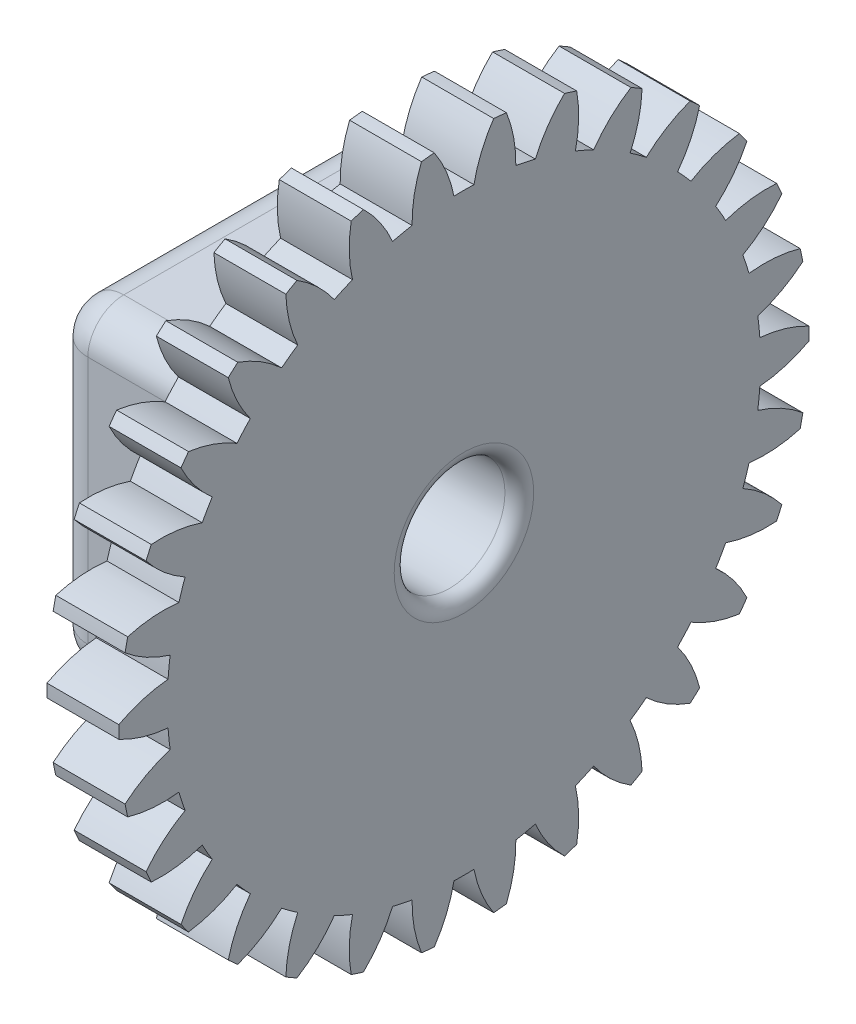
SolidWorks part; units mm, degrees
material "Custom Plastic"
ref_plane "Plane1" through (0, 0, 0) normal (0, 0, 1) x (1, 0, 0)
ref_plane "Plane2" through (0, 0, 0) normal (0, 1, 0) x (1, 0, 0)
ref_plane "Plane3" through (0, 0, 0) normal (1, 0, 0) x (0, 0, -1)
other "Configuration Table"
sketch "HoldingSke" plane through (0, 0, 0) normal (0, 1, 0) x (1, 0, 0)
  line L0 (0, 0) -> (0.2887, -0.1667)
  line L1 (-15, 0) -> (100, 0) construction
  line L2 (0, 0) -> (-2.1039, 2.3779)
  line L3 (0, 0) -> (-11.863, 4.5341)
  line L4 (0, 0) -> (7.479, 4.318)
  line L5 (0, 0) -> (-46.8476, -17.4728)
  line L6 (0, 0) -> (-8.2896, -5.593)
  line L7 (-2.1039, 2.3779) -> (8.6586, 51.2059)
  line L8 (-76.2, 54.61) -> (-74.4, 54.61)
  line L9 (-71.009, 38.7566) -> (-53.1078, 45.2721)
  line L10 (-76.2, 71.12) -> (104.1128, 71.12)
  line L11 (0, 0) -> (-10, 0)
  line L12 (-76.2, 101.6) -> (-76.093, 101.6)
  line L13 (24.9733, 27.94) -> (52.9518, 28.4284)
  line L14 (24.9733, 27.94) -> (24.9743, 27.94)
  line L15 (24.9733, 27.94) -> (100.4006, 29.5858)
  line L16 (-63.627, -3) -> (-12.827, -3)
  circle A0 centre (0, 0) radius 5
  circle A1 centre (0, 0) radius 37.5
  circle A2 centre (0, 0) radius 37.5
  circle A3 centre (0, 0) radius 5
  dimension "MHD" = 75
  dimension "Hub_dia" = 75
  dimension "Bore" = 10
  dimension "MBD" = 10
  dimension "Num_teeth" = 30
  dimension "Pitch" = 0.3333
  dimension "Overall_len" = 50
  dimension "Show_teeth" = 30
  dimension "Thickness" = 10
  dimension "OAL" = 50.0001
  dimension "T_dim" = 1.8
  dimension "Ap" = 20
  dimension "H" = 19.05
  dimension "Pitch_radius" = 180.3128
  dimension "Width" = 10
  dimension "Backlash" = 0.107
  dimension "Addendum_fac" = 1
  dimension "Dedendum_fac" = 1.25
  dimension "Clearance_fac" = 0.25
  dimension "Dedendum_add" = 0.001
  dimension "Module" = 3
sketch "BasProSke" plane through (0, 0, 0) normal (0, 1, 0) x (1, 0, 0)
  line L0 (-10, 0) -> (60, 0) construction
  line L1 (0, 0) -> (0, 48)
  line L2 (0, 0) -> (10, 0)
  line L3 (10, 0) -> (10, 48)
  line L4 (10, 48) -> (0, 48)
  dimension "Thickness" = 10
  dimension "Diameter" = 96
revolve "Base-Revolve" add sketch "BasProSke" angle 360 about L0
sketch "TooCutSke" plane through (0, 0, 0) normal (1, 0, 0) x (0, 0, -1)
  line L1 (0, 0) -> (0, 107) construction
  line L2 (0, 0) -> (-2.5423, 44.9281) construction
  line L3 (0, 0) -> (-9.3966, 89.403) construction
  line L4 (-2.5423, 44.9281) -> (-4.6983, 44.7015) construction
  arc A0 (1.3884, 41.2256) -> (-1.3884, 41.2256) centre (0, 0) ccw
  arc A1 (4.1466, 47.8461) -> (-4.1466, 47.8461) centre (0, 0) ccw
  circle A2 centre (0, 0) radius 45 construction
  circle A3 centre (0, 0) radius 42.2862 construction
  arc A4 (-1.3884, 41.2256) -> (-4.1466, 47.8461) centre (-19.05, 37.752) ccw
  arc A5 (4.1466, 47.8461) -> (1.3884, 41.2256) centre (19.05, 37.752) ccw
  dimension "Root_dia" = 82.498
  dimension "Overcut_dia" = 96.0508
  dimension "Pitch_dia" = 90
  dimension "Base_dia" = 84.5723
  dimension "Flank_rad" = 18
  dimension "Half_ang" = 6
  dimension "Half_CT" = 2.1679
extrude "ToothCut" cut sketch "TooCutSke" along normal through all
fillet "Breaks" [suppressed] radius 0.06
fillet "RootFillets" [suppressed] radius 0.751
pattern_circular "TeethCuts" count 30 every 12 about axis through (-10, 0, 0) along (1, 0, 0) of "ToothCut", "RootFillets", "Breaks"
sketch "HubNeaOneSke" plane through (0, 0, 0) normal (-1, 0, 0) x (0, 0, 1)
  circle A0 centre (0, 0) radius 37.5
  dimension "Diameter" = 75
extrude "HubNearOne" [suppressed] add sketch "HubNeaOneSke" along normal blind 40.0001
sketch "HubNeaBotSke" plane through (0, 0, 0) normal (-1, 0, 0) x (0, 0, 1)
  circle A0 centre (0, 0) radius 37.5
  dimension "Diameter" = 75
extrude "HubNearBoth" [suppressed] add sketch "HubNeaBotSke" along normal blind 20
ref_plane "FarPln" through (10, 0, 0) normal (1, 0, 0) x (0, 0, -1)
sketch "HubFarSke" plane through (10, 0, 0) normal (1, 0, 0) x (0, 0, -1)
  circle A0 centre (0, 0) radius 37.5
  dimension "Diameter" = 75
extrude "HubFar" [suppressed] add sketch "HubFarSke" along normal blind 20
sketch "BorSke" plane through (0, 0, 0) normal (1, 0, 0) x (0, 0, -1)
  circle A0 centre (0, 0) radius 5
  dimension "Diameter" = 10
extrude "Bore" cut sketch "BorSke" along normal mid plane 100.0001
sketch "KeySke" plane through (0, 0, 0) normal (1, 0, 0) x (0, 0, -1)
  line L0 (-2, 0) -> (-2, 6.8)
  line L1 (-2, 6.8) -> (2, 6.8)
  line L2 (2, 6.8) -> (2, 0)
  line L3 (0, 0) -> (0, 34) construction
  line L4 (-2, 0) -> (2, 0)
  dimension "Offset" = 6.8
  dimension "Width" = 4
extrude "Keyway" [suppressed] cut sketch "KeySke" along normal mid plane 100.0001
pattern_circular "Keyway2" [suppressed] count 2 every 90 about axis through (-10, 0, 0) along (1, 0, 0)
sketch "Sketch1" plane through (10, 0, 0) normal (1, 0, 0) x (0, 0, -1)
  circle A0 centre (0, 0) radius 7.7
  dimension "D1" = 15.4
sketch "Sketch2" plane through (0, 0, 0) normal (-1, 0, 0) x (0, 0, 1)
  line L0 (-22.3, 22.3) -> (22.3, -22.3) construction
  line L1 (-22.3, 22.3) -> (22.3, 22.3)
  line L2 (-22.3, 22.3) -> (-22.3, -22.3)
  line L3 (-22.3, -22.3) -> (22.3, -22.3)
  line L4 (22.3, 22.3) -> (22.3, -22.3)
  dimension "D1" = 44.6
extrude "Boss-Extrude1" add sketch "Sketch2" along normal blind 60
extrude "Cut-Extrude1" cut sketch "Sketch1" against normal up to next
sketch "Sketch3" plane through (0, 22.3, 0) normal (0, 1, 0) x (1, 0, 0)
  line L0 (-60, -22.3) -> (0, -22.3) construction
  line L1 (-60, 22.3) -> (-25, 22.3)
  line L2 (-60, 22.3) -> (-60, -22.3)
  line L3 (-60, -22.3) -> (-25, -22.3)
  line L4 (-25, 22.3) -> (-25, -22.3)
  dimension "D1" = 35
extrude "Cut-Extrude2" cut sketch "Sketch3" against normal up to next
fillet "Fillet1" radius 2 2 edges at (10, 0, -7.7) (-25, 0, -7.7)
fillet "Fillet2" radius 5 8 edges at (-25, 0, 22.3) (-25, -22.3, 0) (-25, 0, -22.3) (-25, 22.3, 0) (-12.5, 22.3, -22.3) (-12.5, -22.3, -22.3) (-12.5, -22.3, 22.3) (-12.5, 22.3, 22.3)
equation "' \"Module@HoldingSke\" = 6.35"
equation "' \"Num_teeth@HoldingSke\" = 12"
equation "' \"Ap@HoldingSke\" =  20"
equation "' \"Ap@HoldingSke\" = 20"
equation "' \"Width@HoldingSke\" = 0.5 * 25.4"
equation "' \"Hub_dia@HoldingSke\"= 1 * 25.4"
equation "' \"Hub_dia@HoldingSke\" = 1 * 25.4"
equation "' \"Overall_len@HoldingSke\" = 1.0 * 25.4"
equation "' \"Bore@HoldingSke\" = 0.75 * 25.4"
equation "' \"T_dim@HoldingSke\" = 0.1 * 25.4"
equation "' \"Width@KeySke\" = 0.25 * 25.4"
equation "' \"Show_teeth@HoldingSke\" = 13"
equation "' \"Backlash@HoldingSke\" = 0.009 * 25.4"
equation "' \"Addendum_fac@HoldingSke\" = 1.0"
equation "' \"Dedendum_fac@HoldingSke\" = 1.25"
equation "' \"Dedendum_add@HoldingSke\" = 0.00005 * 25.4"
equation "' \"Clearance_fac@HoldingSke\" = 0.25"
equation "\"Pitch@HoldingSke\" = 1 / \"Module@HoldingSke\""
equation "\"Overcut_dia@TooCutSke\" = (\"Num_teeth@HoldingSke\" + 2 * \"Addendum_fac@HoldingSke\") / \"Pitch@HoldingSke\" + 0.002 * 25.4"
equation "\"Pitch_dia@TooCutSke\" = \"Num_teeth@HoldingSke\" / \"Pitch@HoldingSke\""
equation "\"Base_dia@TooCutSke\" = \"Num_teeth@HoldingSke\" / \"Pitch@HoldingSke\" * cos((\"Ap@HoldingSke\"  * 3.14159265 / 180))"
equation "\"Root_dia@TooCutSke\" = (\"Num_teeth@HoldingSke\" + 2) / \"Pitch@HoldingSke\" - 2 * (\"Addendum_fac@HoldingSke\" + \"Dedendum_fac@HoldingSke\") / \"Pitch@HoldingSke\" - \"Dedendum_add@HoldingSke\" * 2"
equation "\"Half_ang@TooCutSke\" = 180 / \"Num_teeth@HoldingSke\""
equation "\"Half_CT@TooCutSke\" = \"Num_teeth@HoldingSke\" / \"Pitch@HoldingSke\" * sin((3.14159265 / 2 / \"Num_teeth@HoldingSke\")) / 2 - 7 * \"Backlash@HoldingSke\" / 4"
equation "\"Flank_rad@TooCutSke\" = \"Num_teeth@HoldingSke\" / \"Pitch@HoldingSke\" / 5"
equation "\"Radius@RootFillets\" = \"Clearance_fac@HoldingSke\" / \"Pitch@HoldingSke\" + \"Dedendum_add@HoldingSke\""
equation "\"Break_rad@Breaks\" = 0.02 / \"Pitch@HoldingSke\""
equation "\"Thickness@HoldingSke\" = \"Width@HoldingSke\""
equation "\"OAL@HoldingSke\" = \"Thickness@HoldingSke\""
equation "\"MHD@HoldingSke\" = (\"Num_teeth@HoldingSke\" + 2) / \"Pitch@HoldingSke\" - 2 * (\"Addendum_fac@HoldingSke\" + \"Dedendum_fac@HoldingSke\")  / \"Pitch@HoldingSke\" - \"Dedendum_add@HoldingSke\" * 2"
equation "\"MBD@HoldingSke\" = (\"Num_teeth@HoldingSke\" + 2) / \"Pitch@HoldingSke\" - 2 * (\"Addendum_fac@HoldingSke\" + \"Dedendum_fac@HoldingSke\")  / \"Pitch@HoldingSke\" - \"Dedendum_add@HoldingSke\" * 2 - 0.002 * 25.4"
equation "\"MHD@HoldingSke\" = ((sgn( \"MHD@HoldingSke\" - \"Hub_dia@HoldingSke\" )-1)*( \"MHD@HoldingSke\" - \"Hub_dia@HoldingSke\" ))/-2+ \"Hub_dia@HoldingSke\""
equation "\"MBD@HoldingSke\" = ((sgn( \"MBD@HoldingSke\" - \"Bore@HoldingSke\" )-1)*( \"MBD@HoldingSke\" - \"Bore@HoldingSke\" ))/-2+ \"Bore@HoldingSke\""
equation "\"OAL@HoldingSke\" = ((sgn( \"OAL@HoldingSke\" - \"Overall_len@HoldingSke\" )+1)*( \"OAL@HoldingSke\" - \"Overall_len@HoldingSke\" ))/2 + \"Overall_len@HoldingSke\" + 0.000002 * 25.4"
equation "\"Num_teeth@TeethCuts\" = int( \"Show_teeth@HoldingSke\" ) + 1"
equation "\"Num_teeth@TeethCuts\" = ((sgn( \"Num_teeth@TeethCuts\" - \"Num_teeth@HoldingSke\" )-1)*( \"Num_teeth@TeethCuts\" - \"Num_teeth@HoldingSke\" ))/-2+ \"Num_teeth@HoldingSke\""
equation "\"Num_teeth@TeethCuts\" = ((sgn( \"Num_teeth@TeethCuts\" - 2.0)+1)*( \"Num_teeth@TeethCuts\" - 2.0))/2 +2.0"
equation "\"Angle@TeethCuts\" = 360.0 / \"Num_teeth@HoldingSke\""
equation "\"Diameter@BasProSke\" = (\"Num_teeth@HoldingSke\" + 2 * \"Addendum_fac@HoldingSke\") / \"Pitch@HoldingSke\""
equation "\"Thickness@BasProSke\"  = \"Thickness@HoldingSke\""
equation "' \"Fillet_rad@BasProSke\" =  \"Thickness@HoldingSke\" * 0.05"
equation "' \"Fillet_rad@BasProSke\" = \"Thickness@HoldingSke\" * 0.05"
equation "\"MHD@HoldingSke\" = ((sgn( \"MHD@HoldingSke\" - \"Root_dia@TooCutSke\" )-1)*( \"MHD@HoldingSke\" - \"Root_dia@TooCutSke\" ))/-2+ \"Root_dia@TooCutSke\""
equation "\"Diameter@HubNeaOneSke\" = \"MHD@HoldingSke\""
equation "\"Length@HubNearOne\" = \"OAL@HoldingSke\" - \"Thickness@BasProSke\""
equation "\"Diameter@HubNeaBotSke\" = \"MHD@HoldingSke\""
equation "\"Length@HubNearBoth\" = ( \"OAL@HoldingSke\" - \"Thickness@BasProSke\" ) / 2.0"
equation "\"Thickness@FarPln\" = \"Thickness@BasProSke\""
equation "\"Diameter@HubFarSke\" = \"MHD@HoldingSke\""
equation "\"Length@HubFar\" = ( \"OAL@HoldingSke\" - \"Thickness@BasProSke\" ) / 2.0"
equation "\"Diameter@BorSke\" = \"MBD@HoldingSke\""
equation "\"D1@Bore\" = \"OAL@HoldingSke\" * 2.0"
equation "\"D1@Keyway\" = \"OAL@HoldingSke\" * 2.0"
equation "\"Offset@KeySke\" = \"T_dim@HoldingSke\" + \"MBD@HoldingSke\" / 2.0"
